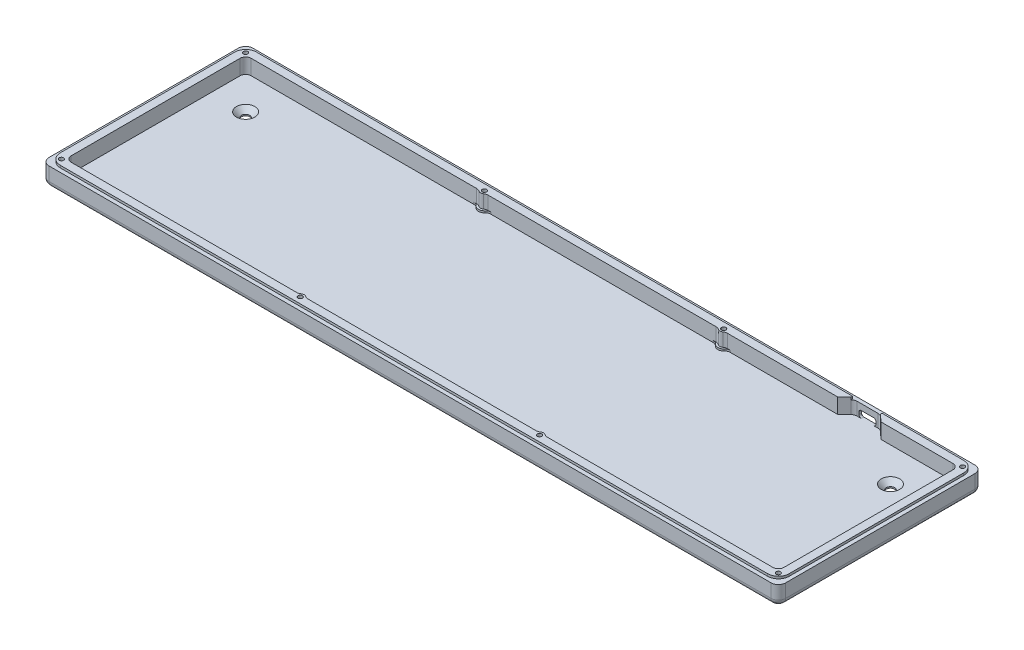
SolidWorks part; units mm, degrees
ref_plane "Front" through (0, 0, 0) normal (0, 0, 1) x (1, 0, 0)
ref_plane "Top" through (0, 0, 0) normal (0, 1, 0) x (1, 0, 0)
ref_plane "Right" through (0, 0, 0) normal (1, 0, 0) x (0, 0, -1)
sketch "Sketch1" plane through (0, 0, 0) normal (0, 1, 0) x (1, 0, 0)
  line L6 (0, 0) -> (-401, 0)
  line L7 (0, 0) -> (0, 111)
  line L8 (0, 111) -> (-401, 111)
  line L9 (-401, 0) -> (-401, 111)
  dimension "D1" = 111
  dimension "D2" = 401
extrude "Boss-Extrude1" add sketch "Sketch1" along normal blind 13.5
sketch "Sketch2" plane through (0, 13.5, 0) normal (0, 1, 0) x (1, 0, 0)
  line L8 (-401, 0) -> (0, 0) construction
  line L9 (-2, 2) -> (-399, 2)
  line L10 (-2, 2) -> (-2, 109)
  line L11 (-2, 109) -> (-399, 109)
  line L12 (-399, 2) -> (-399, 109)
  line L13 (0, 0) -> (0, 111) construction
  line L14 (0, 111) -> (-401, 111) construction
  line L15 (-401, 111) -> (-401, 0) construction
  line L17 (0, 0) -> (-401, 0)
  line L18 (0, 0) -> (0, 111)
  line L19 (0, 111) -> (-401, 111)
  line L20 (-401, 0) -> (-401, 111)
  dimension "D1" = 2
  dimension "D2" = 2
  dimension "D3" = 2
  dimension "D4" = 2
  dimension "D5" = 2
  dimension "D6" = 2
  dimension "D7" = 2
  dimension "D8" = 2
extrude "Cut-Extrude1" cut sketch "Sketch2" against normal blind 1.5
fillet "Fillet1" radius 6 4 edges at (-2, 12.75, -2) (-399, 12.75, -2) (-399, 12.75, -109) (-2, 12.75, -109)
fillet "Fillet2" radius 4 4 edges at (-401, 6, 0) (-401, 6, -111) (0, 6, 0) (0, 6, -111)
sketch "Sketch3" plane through (0, 13.5, 0) normal (0, 1, 0) x (1, 0, 0)
  line L0 (-393, 2) -> (-8, 2) construction
  line L1 (-9.5, 7.5) -> (-391.5, 7.5) construction
  line L2 (-7.5, 9.5) -> (-7.5, 101.5) construction
  line L3 (-9.5, 103.5) -> (-391.5, 103.5) construction
  line L4 (-393.5, 9.5) -> (-393.5, 101.5) construction
  line L5 (-2, 8) -> (-2, 103) construction
  line L7 (-9.5, 6.5) -> (-391.5, 6.5)
  line L8 (-394.5, 9.5) -> (-394.5, 101.5)
  line L9 (-9.5, 104.5) -> (-391.5, 104.5)
  line L10 (-6.5, 9.5) -> (-6.5, 101.5)
  arc A0 (-391.5, 7.5) -> (-393.5, 9.5) centre (-391.5, 9.5) cw construction
  arc A1 (-391.5, 103.5) -> (-393.5, 101.5) centre (-391.5, 101.5) ccw construction
  arc A2 (-7.5, 101.5) -> (-9.5, 103.5) centre (-9.5, 101.5) ccw construction
  arc A3 (-9.5, 7.5) -> (-7.5, 9.5) centre (-9.5, 9.5) ccw construction
  arc A4 (-391.5, 6.5) -> (-394.5, 9.5) centre (-391.5, 9.5) cw
  arc A5 (-391.5, 104.5) -> (-394.5, 101.5) centre (-391.5, 101.5) ccw
  arc A6 (-6.5, 101.5) -> (-9.5, 104.5) centre (-9.5, 101.5) ccw
  arc A7 (-9.5, 6.5) -> (-6.5, 9.5) centre (-9.5, 9.5) ccw
  dimension "D3" = 2
  dimension "D1" = 386
  dimension "D2" = 96
  dimension "D4" = 5.5
  dimension "D5" = 5.5
  dimension "D6" = 1
extrude "Cut-Extrude2" cut sketch "Sketch3" against normal blind 8.5
sketch "Sketch4" plane through (0, 0, 0) normal (0, -1, 0) x (1, 0, 0)
  line L1 (7.4789, -119.629) -> (-418.28, -119.629)
  line L2 (7.4789, -119.629) -> (7.4789, 12.4675)
  line L3 (7.4789, 12.4675) -> (-418.28, 12.4675)
  line L4 (-418.28, -119.629) -> (-418.28, 12.4675)
extrude "Cut-Extrude3" cut sketch "Sketch4" against normal blind 1.5
sketch "Sketch5" plane through (0, 13.5, 0) normal (0, 1, 0) x (1, 0, 0)
  line L2 (-7.5, 92.631) -> (-7.5, 75.6473) construction
  line L3 (-6.5, 9.5) -> (-6.5, 101.5) construction
  line L4 (-73.3928, 103.5) -> (-68.5085, 108.0587)
  line L5 (-66.1204, 109) -> (-54.8796, 109)
  line L6 (-52.4915, 108.0587) -> (-47.6072, 103.5)
  line L7 (-73.3928, 103.5) -> (-47.6072, 103.5)
  line L8 (-9.5, 104.5) -> (-391.5, 104.5) construction
  arc A0 (-54.8796, 109) -> (-52.4915, 108.0587) centre (-54.8796, 105.5) cw
  arc A1 (-68.5085, 108.0587) -> (-66.1204, 109) centre (-66.1204, 105.5) cw
  point P12 (-53.5, 109)
  point P15 (-67.5, 109)
  dimension "D6" = 3.5
  dimension "D1" = 1
  dimension "D2" = 40.1072
  dimension "D3" = 5.8928
  dimension "D4" = 5.8928
  dimension "D5" = 14
  dimension "D7" = 5.5
  dimension "D8" = 1
extrude "Cut-Extrude4" cut sketch "Sketch5" against normal blind 8.5
sketch "Sketch6" plane through (0, 0, -109) normal (0, 0, 1) x (1, 0, 0)
  line L1 (-63.9, 8.75) -> (-57.1, 8.75)
  line L2 (-65.15, 7.5) -> (-65.15, 6.25)
  line L3 (-63.9, 5) -> (-57.1, 5)
  line L4 (-55.85, 7.5) -> (-55.85, 6.25)
  line L5 (-66.1204, 5) -> (-66.1204, 12) construction
  line L6 (-54.8796, 5) -> (-66.1204, 5) construction
  arc A0 (-57.1, 5) -> (-55.85, 6.25) centre (-57.1, 6.25) ccw
  arc A1 (-65.15, 6.25) -> (-63.9, 5) centre (-63.9, 6.25) ccw
  arc A2 (-57.1, 8.75) -> (-55.85, 7.5) centre (-57.1, 7.5) cw
  arc A3 (-63.9, 8.75) -> (-65.15, 7.5) centre (-63.9, 7.5) ccw
  point P4 (-60.5, 8.75)
  dimension "D5" = 1.25
  dimension "D1" = 9.3
  dimension "D2" = 3.75
  dimension "D3" = 5.6204
  dimension "D4" = 0
extrude "Cut-Extrude5" cut sketch "Sketch6" against normal blind 8.5
fillet "Fillet3" radius 3.175 8 edges at (-200.5, 1.5, -111) (-399.8284, 1.5, -109.8284) (-401, 1.5, -55.5) (-399.8284, 1.5, -1.1716) (-200.5, 1.5, 0) (-1.1716, 1.5, -1.1716) (0, 1.5, -55.5) (-1.1716, 1.5, -109.8284)
sketch "Sketch7" plane through (0, 0, -111) normal (0, 0, -1) x (-1, 0, 0)
  line L0 (57.1, 8.75) -> (63.9, 8.75) construction
  line L1 (56.675, 11.125) -> (64.325, 11.125)
  line L2 (53.5, 7.95) -> (53.5, 1.125)
  line L3 (53.5, 1.125) -> (67.5, 1.125)
  line L4 (67.5, 7.95) -> (67.5, 1.125)
  arc A0 (64.325, 11.125) -> (67.5, 7.95) centre (64.325, 7.95) cw
  arc A1 (56.675, 11.125) -> (53.5, 7.95) centre (56.675, 7.95) ccw
  point P6 (60.5, 8.75)
  dimension "D4" = 3.175
  dimension "D1" = 2.375
  dimension "D2" = 14
  dimension "D3" = 7
  dimension "D5" = 10
extrude "Cut-Extrude6" cut sketch "Sketch7" against normal blind 0.375
chamfer "Chamfer1" distance 0.254 angle 45 8 edges at (-60.5, 8.75, -110.625) (-56.2161, 8.3839, -110.625) (-64.7839, 8.3839, -110.625) (-55.85, 6.875, -110.625) (-65.15, 6.875, -110.625) (-56.2161, 5.3661, -110.625) (-64.7839, 5.3661, -110.625) (-60.5, 5, -110.625)
sketch "Sketch8" plane through (0, 0, -109) normal (0, 0, -1) x (-1, 0, 0)
  line L0 (68.5085, 5) -> (68.5085, 13.5) construction
  line L1 (52.4915, 13.5) -> (68.5085, 13.5)
  line L2 (52.4915, 13.5) -> (52.4915, 12)
  line L3 (52.4915, 12) -> (68.5085, 12)
  line L4 (68.5085, 13.5) -> (68.5085, 12)
  line L5 (52.4915, 5) -> (52.4915, 13.5) construction
  line L6 (54.8796, 12) -> (66.1204, 12) construction
  line L7 (8, 13.5) -> (54.8796, 13.5) construction
extrude "Cut-Extrude7" cut sketch "Sketch8" against normal blind 5 and the other way blind 5
sketch "Sketch9" plane through (0, 1.5, 0) normal (0, -1, 0) x (1, 0, 0)
  line L0 (-4, -111) -> (-53.5, -111) construction
  line L1 (0, -4) -> (0, -107) construction
  line L2 (-401, -107) -> (-401, -4) construction
  line L3 (-67.5, -111) -> (-397, -111) construction
  line L4 (-397, -107.825) -> (-4, -107.825) construction
  line L5 (-397.825, -4) -> (-397.825, -107) construction
  circle A0 centre (-200.5, -55.5) radius 37.5
  circle A1 centre (-376, -86) radius 2.5 construction
  circle A2 centre (-25, -86) radius 2.5 construction
  point P17 (-200.5, -107.825)
  point P21 (-397.825, -55.5)
  dimension "D1" = 5
  dimension "D2" = 5
  dimension "D3" = 75
  dimension "D4" = 25
  dimension "D5" = 25
  dimension "D6" = 25
  dimension "D7" = 25
extrude "Cut-Extrude8" cut sketch "Sketch9" against normal blind 10
sketch "Sketch16" plane through (0, 5, 0) normal (0, 1, 0) x (1, 0, 0)
  circle A0 centre (-376, 86) radius 2.5 construction
  circle A1 centre (-25, 86) radius 2.5 construction
  circle A2 centre (-25, 86) radius 2.5 construction
  circle A3 centre (-376, 86) radius 2.5 construction
sketch "Sketch21" plane through (0, 1.5, 0) normal (0, -1, 0) x (1, 0, 0)
  line L0 (-397, -107.825) -> (-4, -107.825) construction
  line L1 (-3.175, -107) -> (-3.175, -4) construction
  line L2 (-4, -3.175) -> (-397, -3.175) construction
  line L3 (-397.825, -4) -> (-397.825, -107) construction
  circle A0 centre (-5.375, -105.625) radius 2.2 construction
  circle A1 centre (-395.625, -105.625) radius 2.2 construction
  circle A2 centre (-395.625, -5.375) radius 2.2 construction
  circle A3 centre (-5.375, -5.375) radius 2.2 construction
  circle A4 centre (-135.375, -105.625) radius 2.2 construction
  circle A5 centre (-135.375, -5.375) radius 2.2 construction
  circle A6 centre (-265.625, -105.625) radius 2.2 construction
  circle A7 centre (-265.625, -5.375) radius 2.2 construction
  dimension "D1" = 4.4
  dimension "D2" = 130
  dimension "D3" = 130
sketch "Sketch25" plane through (0, 5, 0) normal (0, 1, 0) x (1, 0, 0)
  line L0 (-138.3707, 104.5) -> (-132.3793, 104.5)
  line L1 (-268.6207, 104.5) -> (-262.6293, 104.5)
  line L2 (-72.3214, 104.5) -> (-391.5, 104.5) construction
  line L4 (-394.5, 55.5) -> (-140.8376, 55.5) construction
  line L7 (-138.3707, 6.5) -> (-132.3793, 6.5)
  line L8 (-268.6207, 6.5) -> (-262.6293, 6.5)
  line L9 (-394.5, 101.5) -> (-394.5, 9.5) construction
  arc A0 (-138.3707, 104.5) -> (-132.3793, 104.5) centre (-135.375, 105.625) ccw
  circle A1 centre (-135.375, 105.625) radius 2.2 construction
  arc A2 (-138.3707, 6.5) -> (-132.3793, 6.5) centre (-135.375, 5.375) cw
  circle A4 centre (-265.625, 105.625) radius 3.2
  arc A5 (-268.6207, 104.5) -> (-262.6293, 104.5) centre (-265.625, 105.625) ccw
  arc A8 (-268.6207, 6.5) -> (-262.6293, 6.5) centre (-265.625, 5.375) cw
  point P22 (-394.5, 55.5)
  dimension "D1" = 1
  dimension "D2" = 2
extrude "Boss-Extrude4" add sketch "Sketch25" along normal blind 1
fillet "Fillet4" radius 3.175 8 edges at (-132.3793, 5.5, -6.5) (-138.3707, 5.5, -6.5) (-268.6207, 5.5, -6.5) (-262.6293, 5.5, -6.5) (-132.3793, 5.5, -104.5) (-138.3707, 5.5, -104.5) (-262.6293, 5.5, -104.5) (-268.6207, 5.5, -104.5)
sketch "Sketch27" plane through (0, 6, 0) normal (0, 1, 0) x (1, 0, 0)
  line L0 (-394.5, 101.5) -> (-394.5, 9.5) construction
  line L1 (-265.625, 105.625) -> (-265.625, 103.5) construction
  line L2 (-260.9186, 104.5) -> (-270.3314, 104.5) construction
  line L3 (-267.4278, 104.5) -> (-263.8222, 104.5)
  line L4 (-137.1778, 104.5) -> (-133.5722, 104.5)
  line L5 (-200.5, 55.5) -> (-150.6671, 55.5) construction
  line L6 (-137.1778, 6.5) -> (-133.5722, 6.5)
  line L7 (-267.4278, 6.5) -> (-263.8222, 6.5)
  arc A0 (-267.4278, 104.5) -> (-263.8222, 104.5) centre (-265.625, 105.625) ccw
  arc A1 (-137.1778, 104.5) -> (-133.5722, 104.5) centre (-135.375, 105.625) ccw
  circle A2 centre (-135.375, 105.625) radius 2.2 construction
  arc A3 (-137.1778, 6.5) -> (-133.5722, 6.5) centre (-135.375, 5.375) cw
  arc A4 (-267.4278, 6.5) -> (-263.8222, 6.5) centre (-265.625, 5.375) cw
  point P24 (-394.5, 55.5)
  dimension "D1" = 1
  dimension "D2" = 2
extrude "Boss-Extrude5" add sketch "Sketch27" along normal up to surface (7.5 mm away) up to face at (-162.3182, 13.5, -69.5962)
hole_wizard "CBORE for M2 SHCS2" positions "3DSketch4" profile "Sketch28" counterbore size "M2" standard "ANSI Metric" end condition through all
sketch3d "3DSketch4"
  point P0 (-5.375, 1.5, -105.625)
  point P3 (-135.375, 1.5, -105.625)
  point P6 (-265.625, 1.5, -105.625)
  point P9 (-395.625, 1.5, -105.625)
  point P12 (-395.625, 1.5, -5.375)
  point P15 (-265.625, 1.5, -5.375)
  point P18 (-135.375, 1.5, -5.375)
  point P21 (-5.375, 1.5, -5.375)
sketch "Sketch28" plane through (-5.375, 1.5, -105.625) normal (1, 0, 0) x (0, 0, -1)
  line L0 (0, 0) -> (0, 12)
  line L1 (0, 12) -> (1.2, 12)
  line L3 (1.2, 12) -> (1.2, 2.3)
  line L4 (1.2, 2.3) -> (2.2, 2.3)
  line L5 (2.2, 2.3) -> (2.2, 0)
  line L7 (2.2, 0) -> (0, 0)
  line L11 (0, -6.35) -> (0, 107.95) construction
  dimension "Thru Hole Dia." = 2.4
  dimension "Thru Hole Depth" = 12
  dimension "C'Bore Dia." = 4.4
  dimension "C'Bore Depth" = 2.3
sketch "Sketch33" plane through (0, 13.5, 0) normal (0, 1, 0) x (1, 0, 0)
  line L1 (14.1776, -13.9498) -> (-413.2792, -13.9498)
  line L2 (14.1776, -13.9498) -> (14.1776, 120.2038)
  line L3 (14.1776, 120.2038) -> (-413.2792, 120.2038)
  line L4 (-413.2792, -13.9498) -> (-413.2792, 120.2038)
extrude "Cut-Extrude9" cut sketch "Sketch33" against normal blind 0.25
sketch "Sketch37" plane through (0, 5, 0) normal (0, 1, 0) x (1, 0, 0)
  circle A0 centre (-200.5, 55.5) radius 45
  dimension "D1" = 90
extrude "Boss-Extrude6" add sketch "Sketch37" against normal blind 1.1
hole_wizard "CSK for M4 Flat Head Machine Screw1" positions "3DSketch5" profile "Sketch38" countersink size "M4" standard "ANSI Metric" end condition through all
sketch3d "3DSketch5"
  point P0 (-376, 5, -86)
  point P3 (-25, 5, -86)
sketch "Sketch38" plane through (-376, 5, -86) normal (1, 0, 0) x (0, 0, 1)
  line L0 (0, 0) -> (0, 3.5)
  line L1 (0, 3.5) -> (2.25, 3.5)
  line L2 (2.25, 3.5) -> (2.25, 2.75)
  line L3 (2.25, 2.75) -> (5, 0)
  line L5 (5, 0) -> (0, 0)
  line L6 (-2.25, 2.75) -> (-5, 0) construction
  line L11 (0, -6.35) -> (0, 107.95) construction
  dimension "Thru Hole Dia." = 4.5
  dimension "Thru Hole Depth" = 3.5
  dimension "Near C'Sink Dia." = 10
  dimension "Near C'Sink Angle" = 90
fillet "Fillet5" radius 3.175 8 edges at (-133.5722, 9.625, -6.5) (-137.1778, 9.625, -6.5) (-263.8222, 9.625, -6.5) (-267.4278, 9.625, -6.5) (-137.1778, 9.625, -104.5) (-133.5722, 9.625, -104.5) (-267.4278, 9.625, -104.5) (-263.8222, 9.625, -104.5)
sketch "Sketch40" plane through (0, 13.25, 0) normal (0, 1, 0) x (1, 0, 0)
  line L26 (-415.8135, 130.4408) -> (56.4583, 130.4408)
  line L27 (-415.8135, 130.4408) -> (-415.8135, -43.6199)
  line L28 (-415.8135, -43.6199) -> (56.4583, -43.6199)
  line L29 (56.4583, 130.4408) -> (56.4583, -43.6199)
  line L30 (-52.4915, 108.875) -> (-8, 108.875)
  line L31 (-2.125, 103) -> (-2.125, 8)
  line L32 (-8, 2.125) -> (-393, 2.125)
  line L33 (-398.875, 8) -> (-398.875, 103)
  line L34 (-393, 108.875) -> (-68.5085, 108.875)
  line L35 (-52.4915, 108.875) -> (-8, 108.875)
  line L36 (-2.125, 103) -> (-2.125, 8)
  line L37 (-8, 2.125) -> (-393, 2.125)
  line L38 (-398.875, 8) -> (-398.875, 103)
  line L39 (-393, 108.875) -> (-52.4915, 108.875)
  arc A24 (-2.125, 103) -> (-8, 108.875) centre (-8, 103) ccw
  arc A25 (-8, 2.125) -> (-2.125, 8) centre (-8, 8) ccw
  arc A26 (-398.875, 8) -> (-393, 2.125) centre (-393, 8) ccw
  arc A27 (-393, 108.875) -> (-398.875, 103) centre (-393, 103) ccw
  arc A28 (-2.125, 103) -> (-8, 108.875) centre (-8, 103) ccw
  arc A29 (-8, 2.125) -> (-2.125, 8) centre (-8, 8) ccw
  arc A30 (-398.875, 8) -> (-393, 2.125) centre (-393, 8) ccw
  arc A31 (-393, 108.875) -> (-398.875, 103) centre (-393, 103) ccw
  dimension "D1" = 0.125
extrude "Cut-Extrude10" cut sketch "Sketch40" against normal up to surface (1.25 mm away) up to face at (-140.5, 12, -78.3265)
